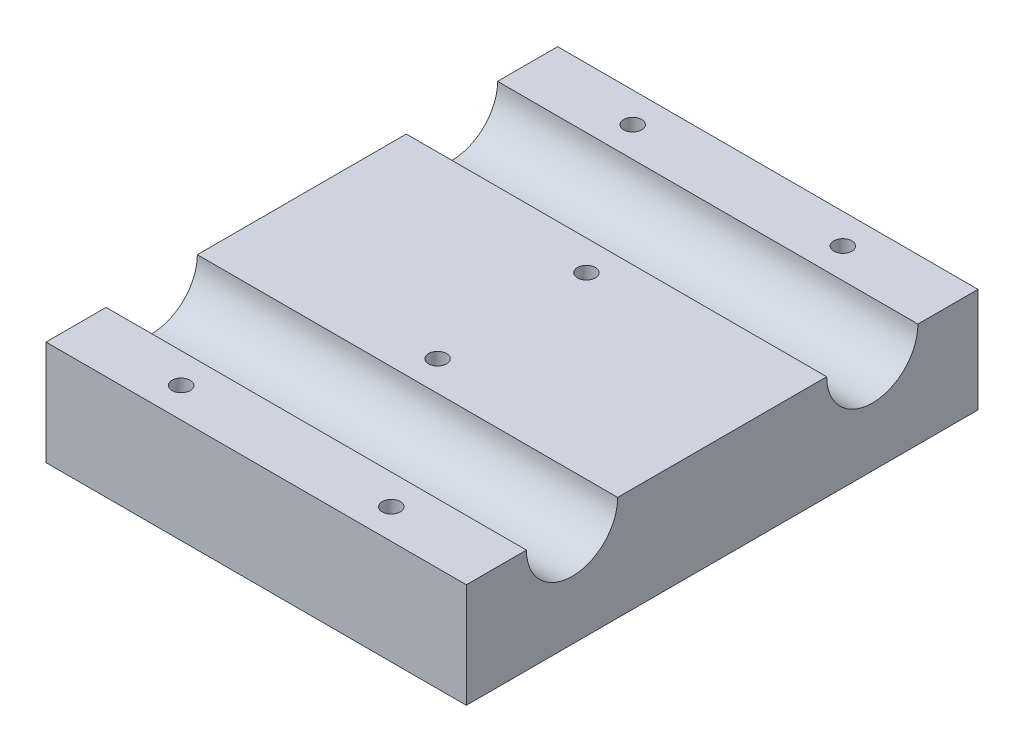
SolidWorks part; units mm, degrees
material "ABS"
ref_plane "Front Plane" through (0, 0, 0) normal (1, 0, 0) x (0, 1, 0)
ref_plane "Top Plane" through (0, 0, 0) normal (0, 0, 1) x (0, 1, 0)
ref_plane "Right Plane" through (0, 0, 0) normal (0, 1, 0) x (-1, 0, 0)
sketch "Sketch1" plane through (0, 0, 0) normal (1, 0, 0) x (0, 1, 0)
  line L0 (17.3907, -10) -> (17.3907, -25.2) construction
  line L1 (0, 0) -> (17.3907, 0)
  line L2 (0, 0) -> (0, -85.2)
  line L3 (0, -85.2) -> (17.3907, -85.2)
  line L4 (17.3907, 0) -> (17.3907, -10)
  line L5 (17.3907, -25.2) -> (17.3907, -60)
  line L6 (17.3907, -60) -> (17.3907, -75.2) construction
  line L7 (17.3907, -75.2) -> (17.3907, -85.2)
  arc A0 (17.3907, -10) -> (17.3907, -25.2) centre (17.3907, -17.6) ccw
  arc A1 (17.3907, -60) -> (17.3907, -75.2) centre (17.3907, -67.6) ccw
  arc A2 (17.3907, -25.2) -> (17.3907, -10) centre (17.3907, -17.6) ccw construction
  arc A3 (17.3907, -75.2) -> (17.3907, -60) centre (17.3907, -67.6) ccw construction
  point P6 (52.6157, -21.4269)
  point P8 (26.547, -12.6)
  point P9 (0, 0)
  point P10 (62.4643, -33.6211)
  point P11 (63.9729, -49.7632)
  point P12 (57.7683, -22.1895)
  point P13 (63.0677, -19.4703)
  point P14 (56.9126, -71.4269)
  point P15 (0, 0)
  point P16 (56.7315, -21.4269)
  point P17 (53.2919, -21.4269)
  dimension "D4" = 7.6
  dimension "D1" = 50
  dimension "D2" = 10
  dimension "D3" = 10
extrude "Boss-Extrude1" add sketch "Sketch1" along normal blind 70 contours A1 L5 A0 L4 L1 L2 L3 L7
sketch "Sketch2" plane through (0, 17.3907, 0) normal (0, 1, 0) x (-1, 0, 0)
  line L0 (-70, -5) -> (0, -5) construction
  line L1 (-70, 0) -> (-70, -10) construction
  line L2 (0, 0) -> (0, -10) construction
  line L3 (-35, 0) -> (-35, -10) construction
  line L4 (-70, 0) -> (0, 0) construction
  line L5 (-70, -10) -> (0, -10) construction
  line L6 (-70, -80.2) -> (0, -80.2) construction
  line L7 (-70, -75.2) -> (-70, -85.2) construction
  line L8 (0, -75.2) -> (0, -85.2) construction
  line L9 (-35, -75.2) -> (-35, -85.2) construction
  line L10 (-70, -75.2) -> (0, -75.2) construction
  line L11 (-70, -85.2) -> (0, -85.2) construction
  line L12 (-35, -10) -> (-35, -75.2) construction
  line L13 (-70, -25.2) -> (0, -25.2) construction
  line L14 (-70, -60) -> (0, -60) construction
  circle A0 centre (-52.5, -5) radius 1.5
  circle A1 centre (-17.5, -5) radius 1.5
  circle A2 centre (-52.5, -80.2) radius 1.5
  circle A3 centre (-17.5, -80.2) radius 1.5
  circle A4 centre (-35, -30.2) radius 1.5
  circle A5 centre (-35, -55) radius 1.5
  point P10 (-35, -5)
  dimension "D1" = 3
  dimension "D2" = 3
  dimension "D5" = 3
  dimension "D3" = 17.5
  dimension "D4" = 17.5
  dimension "D6" = 17.5
  dimension "D7" = 17.5
  dimension "D8" = 5
  dimension "D9" = 5
  dimension "D10" = 5
extrude "Cut-Extrude1" cut sketch "Sketch2" against normal up to surface (17.3907 mm away) up to face at (35, 0, -42.6)
equation "\"screw_hole\"= 3mm"
equation "\"offset\"= 2.52mm"
equation "\"y_length\" = 40mm"
equation "\"z_breadth\"= 29mm"
equation "\"lm8uu_bearing_dia\"= 15.2mm"
equation "\"x_steel_rods_gap\"= 50mm"
equation "\"D1@Sketch1\"=\"x_steel_rods_gap\""
equation "\"D3@Sketch1\"=\"D2@Sketch1\""
equation "\"D1@Boss-Extrude1\"=\"b\""
equation "\"D2@Boss-Extrude1\"=\"y_length\"/2"
equation "\"D4@Sketch1\"=\"lm8uu_bearing_dia\"/2"
equation "\"a\"= 10mm"
equation "\"b\"= 70mm"
equation "\"D2@Sketch1\"=\"a\""
equation "\"D1@Sketch2\"=\"screw_hole\""
equation "\"D2@Sketch2\"=\"screw_hole\""
equation "\"D3@Sketch2\"=\"b\"/4"
equation "\"D4@Sketch2\"=\"D3@Sketch2\""
equation "\"D5@Sketch2\"=\"screw_hole\""
equation "\"D6@Sketch2\"=\"D4@Sketch2\""
equation "\"D7@Sketch2\"=\"D6@Sketch2\""
equation "\"D9@Sketch2\"=\"a\"/2"
equation "\"D10@Sketch2\"=\"a\"/2"
